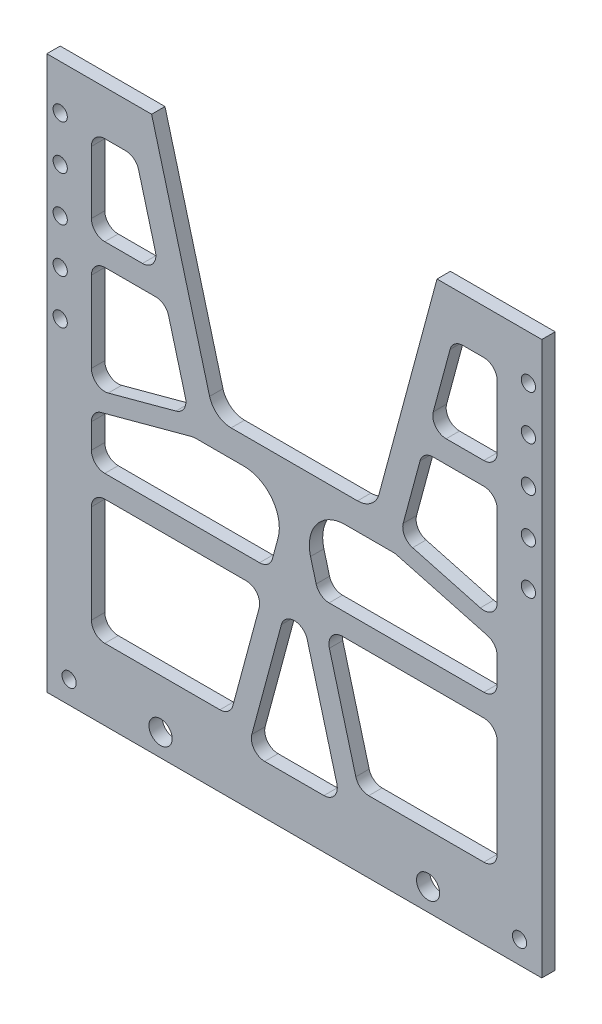
SolidWorks part; units mm, degrees
material "环氧树脂FR-4"
ref_plane "前视基准面" through (0, 0, 0) normal (0, 0, 1) x (1, 0, 0)
ref_plane "上视基准面" through (0, 0, 0) normal (0, 1, 0) x (1, 0, 0)
ref_plane "右视基准面" through (0, 0, 0) normal (1, 0, 0) x (0, 0, -1)
sketch "草图1" plane through (0, 0, 0) normal (0, 0, 1) x (1, 0, 0)
  line L0 (0, 0) -> (0, -62) construction
  line L1 (55.5, -62) -> (-55.5, -62)
  line L2 (55.5, -62) -> (55.5, 62)
  line L3 (55.5, 62) -> (-55.5, 62)
  line L4 (-55.5, -62) -> (-55.5, 62)
  line L5 (55.5, -62) -> (-55.5, 62) construction
  line L6 (55.5, 62) -> (-55.5, -62) construction
  line L7 (-50.5, -57) -> (-30, -57) construction
  circle A0 centre (-30, -57) radius 2.6
  circle A1 centre (-50.5, -57) radius 1.6
  circle A2 centre (30, -57) radius 2.6
  circle A3 centre (50.5, -57) radius 1.6
  point P0 (0, 0)
  dimension "D5" = 3.2
  dimension "D6" = 5.2
  dimension "D7" = 60
  dimension "D1" = 124
  dimension "D2" = 111
  dimension "D3" = 5
  dimension "D4" = 5
extrude "凸台-拉伸1" add sketch "草图1" along normal blind 3
sketch "草图2" plane through (0, 0, 3) normal (0, 0, 1) x (1, 0, 0)
  line L0 (-52.5, 42) -> (-52.5, 22) construction
  line L1 (-55.5, -62) -> (55.5, -62) construction
  line L3 (-55.5, 62) -> (-55.5, -62) construction
  line L4 (-52.5, 52) -> (-52.5, 42) construction
  line L5 (-52.5, 22) -> (-52.5, 12) construction
  line L6 (0, 0) -> (0, -62) construction
  circle A0 centre (-52.5, 22) radius 1.6
  circle A1 centre (-52.5, 42) radius 1.6
  circle A2 centre (-52.5, 32) radius 1.6
  circle A3 centre (-52.5, 52) radius 1.6
  circle A4 centre (-52.5, 12) radius 1.6
  circle A5 centre (52.5, 12) radius 1.6
  circle A6 centre (52.5, 52) radius 1.6
  circle A7 centre (52.5, 32) radius 1.6
  circle A8 centre (52.5, 42) radius 1.6
  circle A9 centre (52.5, 22) radius 1.6
  dimension "D1" = 3.2
  dimension "D3" = 20
  dimension "D4" = 3
  dimension "D5" = 10
  dimension "D2" = 84
  dimension "D6" = 10
extrude "切除-拉伸1" cut sketch "草图2" against normal through all
sketch "草图5" plane through (0, 0, 0) normal (0, 0, -1) x (-1, 0, 0)
  line L0 (0, 62) -> (0, 0) construction
  line L1 (-55.5, 62) -> (55.5, 62) construction
  line L2 (-32, 62) -> (-18, 10)
  line L3 (-18, 10) -> (18, 10)
  line L4 (32, 62) -> (18, 10)
  line L5 (-32, 62) -> (32, 62)
  point P9 (0, 10)
  dimension "D1" = 32
  dimension "D2" = 52
  dimension "D3" = 18
extrude "切除-拉伸3" cut sketch "草图5" against normal through all
sketch "草图6" plane through (0, 0, 0) normal (0, 0, -1) x (-1, 0, 0)
  line L0 (-35.5213, 52) -> (-30.1367, 32)
  line L1 (-22.5983, 4) -> (-0.9231, 4)
  line L2 (-0.9231, 4) -> (-5.5, -13)
  line L3 (-35.5213, 52) -> (-45.5, 52)
  line L4 (-45.5, 52) -> (-45.5, 32)
  line L5 (-45.5, -13) -> (-5.5, -13)
  line L6 (-45.5, 32) -> (-30.1367, 32)
  line L7 (-45.5, 27) -> (-28.7906, 27)
  line L8 (-28.7906, 27) -> (-22.5983, 4)
  line L9 (-45.5, 27) -> (-45.5, -13)
  line L10 (0, 0) -> (0, -62) construction
  line L11 (55.5, -62) -> (-55.5, -62) construction
  line L12 (-10.5527, -51) -> (0, -11.8042)
  line L13 (-10.5527, -51) -> (10.5527, -51)
  line L14 (-55.5, 62) -> (-32, 62) construction
  line L15 (-55.5, -62) -> (-55.5, 62) construction
  line L16 (-32, 62) -> (-18, 10) construction
  line L17 (18, 10) -> (32, 62) construction
  line L18 (-6.8462, -18) -> (-14.3846, -46)
  line L19 (-14.3846, -46) -> (-45.5, -46)
  line L20 (-45.5, -46) -> (-45.5, -18)
  line L21 (-45.5, -18) -> (-6.8462, -18)
  line L22 (-18, 10) -> (18, 10) construction
  line L23 (10.5527, -51) -> (0, -11.8042)
  line L24 (45.5, -46) -> (45.5, -18)
  line L25 (14.3846, -46) -> (45.5, -46)
  line L26 (6.8462, -18) -> (14.3846, -46)
  line L27 (45.5, -18) -> (6.8462, -18)
  line L28 (35.5213, 52) -> (45.5, 52)
  line L29 (45.5, 52) -> (45.5, 32)
  line L30 (45.5, 32) -> (30.1367, 32)
  line L31 (35.5213, 52) -> (30.1367, 32)
  line L32 (22.5983, 4) -> (0.9231, 4)
  line L33 (28.7906, 27) -> (22.5983, 4)
  line L34 (45.5, 27) -> (28.7906, 27)
  line L35 (45.5, 27) -> (45.5, -13)
  line L36 (45.5, -13) -> (5.5, -13)
  line L37 (0.9231, 4) -> (5.5, -13)
  line L38 (-45.5, 1.9766) -> (-23.6382, 7.8625)
  line L39 (-45.5, -2.1659) -> (-22.5983, 4)
  line L40 (45.5, -2.1659) -> (22.5983, 4)
  line L41 (45.5, 1.9766) -> (23.6382, 7.8625)
  point P33 (0, -51)
  dimension "D1" = 10
  dimension "D2" = 20
  dimension "D3" = 5
  dimension "D4" = 6
  dimension "D5" = 10
  dimension "D6" = 6
  dimension "D7" = 40
  dimension "D8" = 5
  dimension "D9" = 40
  dimension "D10" = 5
  dimension "D11" = 16
  dimension "D12" = 11
  dimension "D13" = 4
extrude "切除-拉伸4" cut sketch "草图6" against normal through all contours L4 L6 L0 L3 | L9 L38 L8 L7 | L39 L9 L5 L2 L1 | L35 L40 L32 L37 L36 | L41 L35 L34 L33 | L28 L31 L30 L29 | L24 L27 L26 L25 | L21 L20 L19 L18 | L23 L10 L13 | L10 L12 L13
fillet "圆角1" radius 8 2 edges at (-0.9231, 4, 1.5) (0.9231, 4, 1.5)
fillet "圆角2" radius 3 35 edges at (5.5, -13, 1.5) (45.5, -13, 1.5) (45.5, -2.1659, 1.5) (-28.7906, 27, 1.5) (-45.5, 27, 1.5) (-45.5, 1.9766, 1.5) (-23.6382, 7.8625, 1.5) (-5.5, -13, 1.5) (-22.5983, 4, 1.5) (-45.5, -2.1659, 1.5) (-45.5, -13, 1.5) (14.3846, -46, 1.5) (45.5, -46, 1.5) (45.5, -18, 1.5) (6.8462, -18, 1.5) (-45.5, 32, 1.5) (-30.1367, 32, 1.5) (-35.5213, 52, 1.5) (-45.5, 52, 1.5) (45.5, 52, 1.5) (35.5213, 52, 1.5) (30.1367, 32, 1.5) (45.5, 32, 1.5) (-45.5, -46, 1.5) (-14.3846, -46, 1.5) (-6.8462, -18, 1.5) (-45.5, -18, 1.5) (-10.5527, -51, 1.5) (10.5527, -51, 1.5) (0, -11.8042, 1.5) (45.5, 27, 1.5) (28.7906, 27, 1.5) (23.6382, 7.8625, 1.5) (45.5, 1.9766, 1.5) (22.5983, 4, 1.5)
fillet "圆角3" radius 5 2 edges at (-18, 10, 1.5) (18, 10, 1.5)
